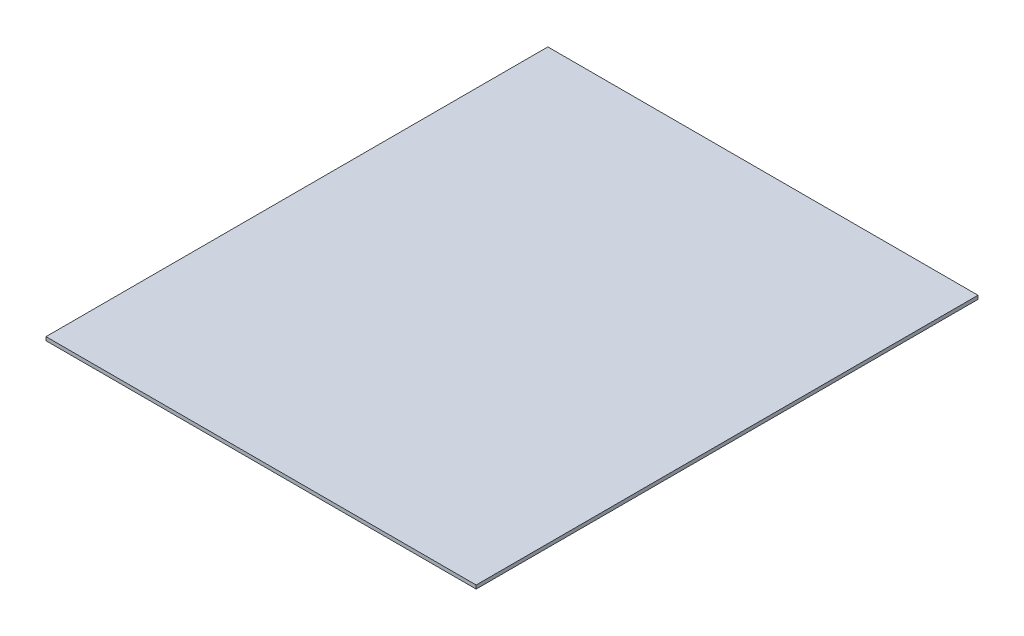
SolidWorks part; units mm, degrees
ref_plane "Front Plane" through (0, 0, 0) normal (0, 0, 1) x (1, 0, 0)
ref_plane "Top Plane" through (0, 0, 0) normal (0, 1, 0) x (1, 0, 0)
ref_plane "Right Plane" through (0, 0, 0) normal (1, 0, 0) x (0, 0, -1)
sketch "Sketch1" plane through (0, 0, 0) normal (0, 1, 0) x (1, 0, 0)
  line L5 (0, 0) -> (240, 0)
  line L6 (0, 0) -> (0, 280)
  line L7 (0, 280) -> (240, 280)
  line L8 (240, 0) -> (240, 280)
  dimension "D1" = 280
  dimension "D2" = 240
extrude "Boss-Extrude1" add sketch "Sketch1" along normal blind 2
